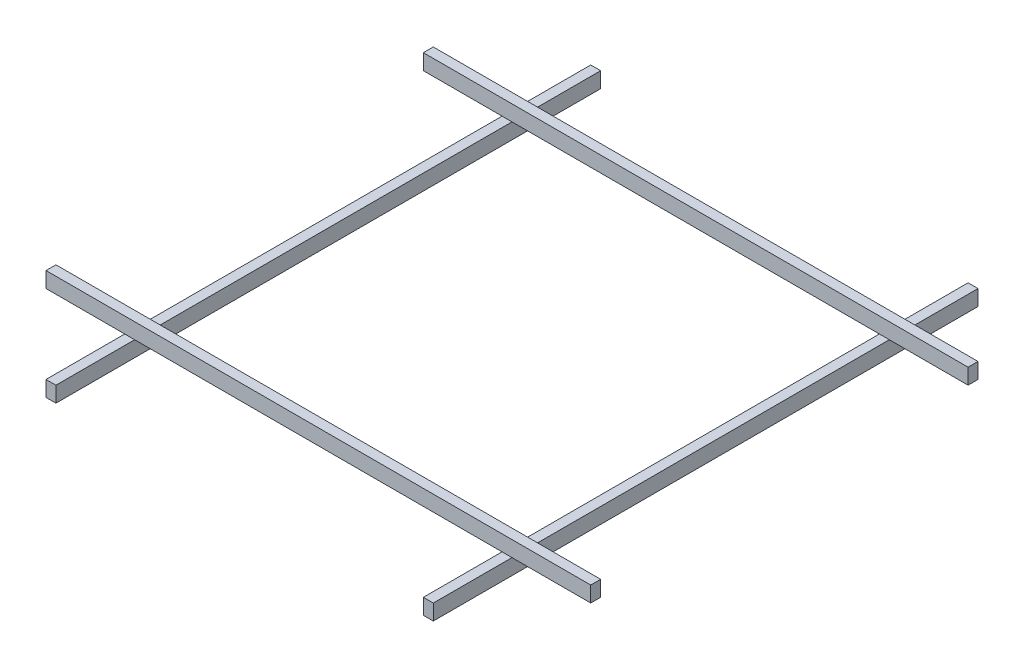
SolidWorks part; units mm, degrees
material "Doug Fir"
ref_plane "Front Plane" through (0, 0, 0) normal (0, 0, 1) x (1, 0, 0)
ref_plane "Top Plane" through (0, 0, 0) normal (0, 1, 0) x (1, 0, 0)
ref_plane "Right Plane" through (0, 0, 0) normal (1, 0, 0) x (0, 0, -1)
sketch "Lower Level" plane through (0, 0, 0) normal (0, 1, 0) x (1, 0, 0)
  line L0 (444.5, 0) -> (444.5, 4876.8)
  line L1 (3822.7, 0) -> (3822.7, 4876.8)
  line L2 (444.5, 2438.4) -> (3822.7, 2438.4) construction
  point P7 (2133.6, 2438.4)
  dimension "D1" = 4876.8
  dimension "D2" = 1689.1
ref_plane "Plane2" through (0, 139.7, 0) normal (0, 1, 0) x (1, 0, 0)
sketch "Sketch12" plane through (0, 139.7, 0) normal (0, 1, 0) x (1, 0, 0)
  line L0 (-304.8, 4127.5) -> (4572, 4127.5)
  line L1 (4572, 749.3) -> (-304.8, 749.3)
  line L2 (2133.6, 4127.5) -> (2133.6, 749.3) construction
  point P0 (2133.6, 2438.4)
  point P6 (2133.6, 749.3)
  point P7 (2133.6, 4127.5)
  point P10 (2133.6, 2438.4)
  dimension "D1" = 4876.8
  dimension "D2" = 1689.1
other "Profiles 4X6(1)"
ref_plane "Plane1" through (444.5, 0, 0) normal (0, 0, -1) x (-1, 0, 0)
sketch "Sketch1" plane through (444.5, 0, 0) normal (0, 0, -1) x (-1, 0, 0)
  line L1 (-44.45, 69.85) -> (44.45, 69.85)
  line L2 (-44.45, 69.85) -> (-44.45, -69.85)
  line L3 (-44.45, -69.85) -> (44.45, -69.85)
  line L4 (44.45, 69.85) -> (44.45, -69.85)
  line L5 (-44.45, 69.85) -> (44.45, -69.85) construction
  line L6 (-44.45, -69.85) -> (44.45, 69.85) construction
  point P0 (0, 0)
  point P6 (0, 69.85)
  point P7 (0, -69.85)
  point P8 (44.45, 0)
  point P9 (-44.45, 0)
  point P10 (0, 0)
  dimension "D1" = 88.9
  dimension "D2" = 139.7
sketch3d "3DSketch2"
  line L0 (2133.6, 139.7, -2438.4) -> (2133.6, 0, -2438.4)
  line L1 (444.5, 0, -2438.4) -> (3822.7, 0, -2438.4) construction
equation "\"Width\" = 66.5"
equation "\"Length\"=192"
equation "\"D1@Lower Level\"=\"Length\""
equation "\"D2@Lower Level\"=\"Width\""
equation "\"D1@Sketch12\"=\"Length\""
equation "\"D2@Sketch12\"=\"Width\""
